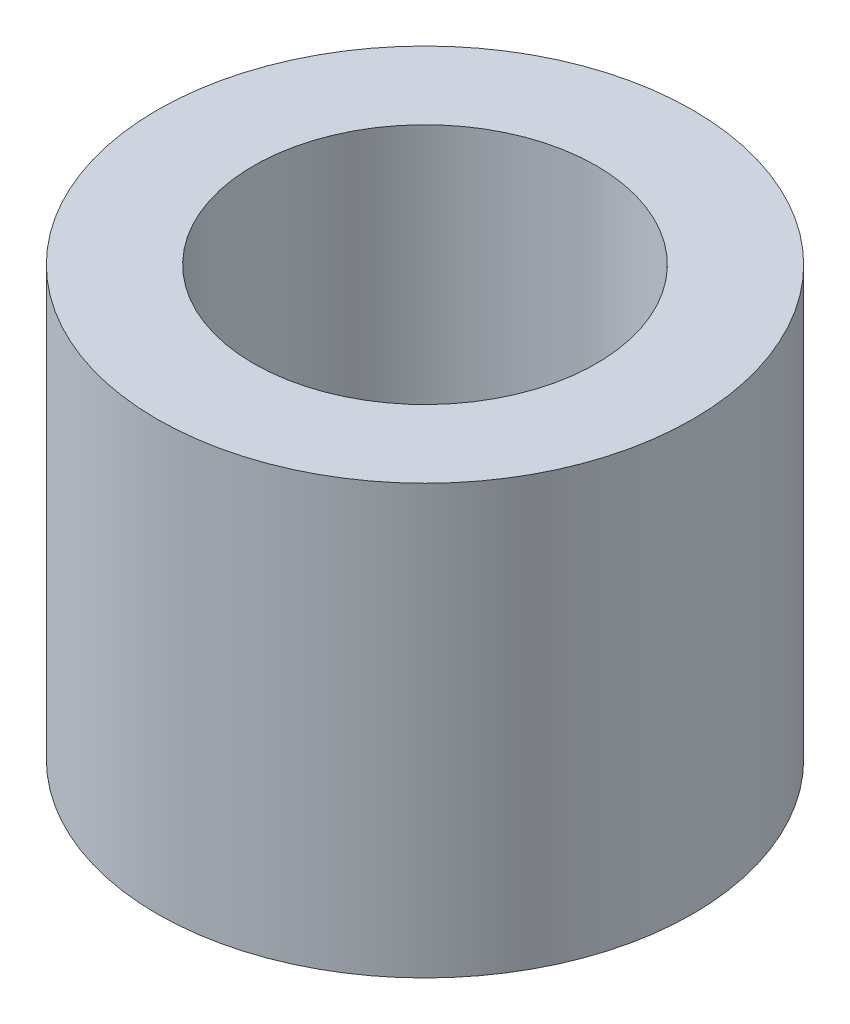
SolidWorks part; units mm, degrees
ref_plane "前视基准面" through (0, 0, 0) normal (0, 0, 1) x (1, 0, 0)
ref_plane "上视基准面" through (0, 0, 0) normal (0, 1, 0) x (1, 0, 0)
ref_plane "右视基准面" through (0, 0, 0) normal (1, 0, 0) x (0, 0, -1)
other "Configuration Table"
sketch "草图1" plane through (0, 0, 0) normal (0, 1, 0) x (1, 0, 0)
  circle A0 centre (0, 0) radius 1.6
  circle A1 centre (0, 0) radius 2.5
  dimension "D1" = 3.2
  dimension "D2" = 5
extrude "凸台-拉伸1" add sketch "草图1" along normal blind 4
